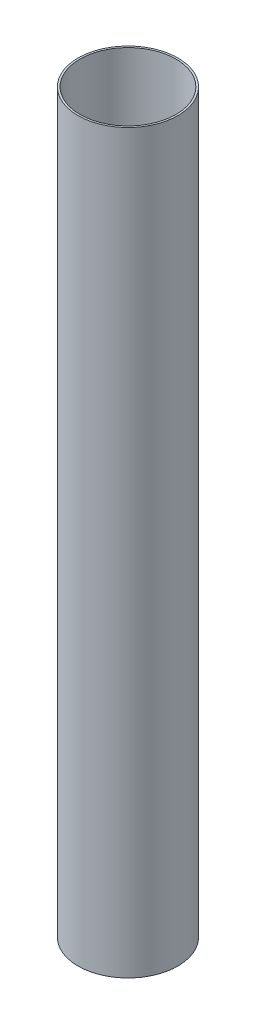
SolidWorks part; units mm, degrees
material "S-Glass Fiber"
ref_plane "Front Plane" through (0, 0, 0) normal (0, 0, 1) x (1, 0, 0)
ref_plane "Top Plane" through (0, 0, 0) normal (0, 1, 0) x (1, 0, 0)
ref_plane "Right Plane" through (0, 0, 0) normal (1, 0, 0) x (0, 0, -1)
sketch "Sketch4" plane through (0, 0, 0) normal (0, 1, 0) x (1, 0, 0)
  circle A0 centre (-10.0305, 2.7128) radius 39.6
  circle A1 centre (-10.0305, 2.7128) radius 38.1
  dimension "D1" = 79.2
  dimension "D2" = 76.2
extrude "Boss-Extrude2" add sketch "Sketch4" along normal blind 584.2
